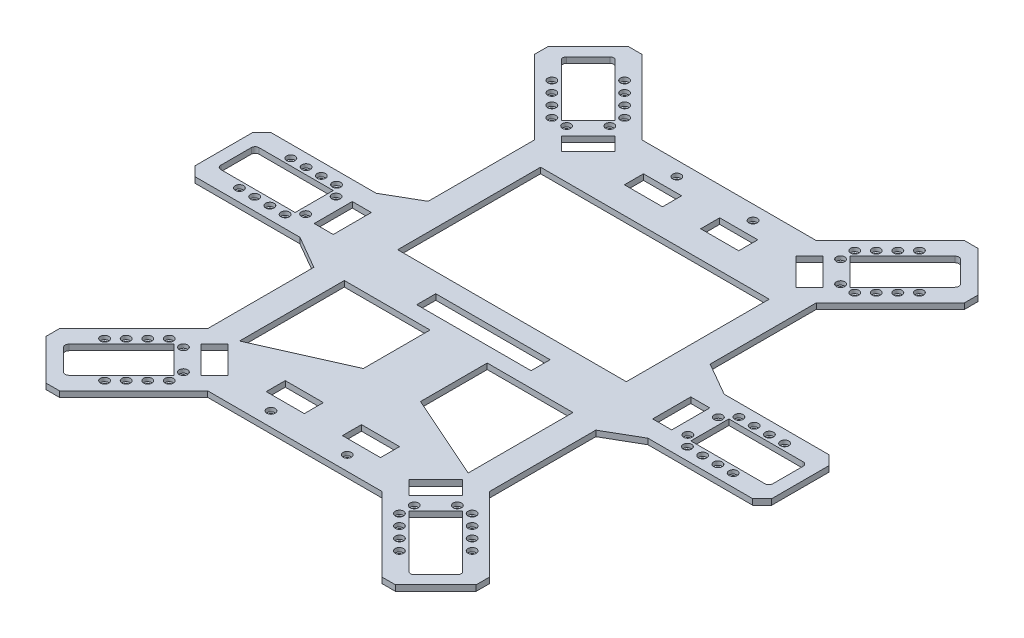
SolidWorks part; units mm, degrees
ref_plane "Front" through (0, 0, 0) normal (0, 0, 1) x (1, 0, 0)
ref_plane "Top" through (0, 0, 0) normal (0, 1, 0) x (1, 0, 0)
ref_plane "Right" through (0, 0, 0) normal (1, 0, 0) x (0, 0, -1)
sketch "草图1" plane through (0, 0, 0) normal (0, 1, 0) x (1, 0, 0)
  line L0 (-45.7157, 114) -> (45.7157, 114)
  line L1 (-74, 0) -> (74, 0) construction
  line L2 (74, -30) -> (91.3205, -20)
  line L3 (91.3205, -20) -> (146.3205, -20)
  line L4 (151.3205, -15) -> (151.3205, 15)
  line L5 (-60, 100) -> (60, -100) construction
  line L6 (-60, -100) -> (60, 100) construction
  line L7 (74, -30) -> (74, -85.7157)
  line L8 (-45.7157, -114) -> (45.7157, -114)
  line L9 (-74, 85.7157) -> (-74, 30)
  line L10 (146.3205, 20) -> (91.3205, 20)
  line L11 (74, 30) -> (91.3205, 20)
  line L12 (0, 100) -> (0, -100) construction
  line L13 (-74, 30) -> (-91.3205, 20)
  line L14 (-146.3205, 20) -> (-91.3205, 20)
  line L15 (-151.3205, -15) -> (-151.3205, 15)
  line L16 (-91.3205, -20) -> (-146.3205, -20)
  line L17 (-74, -30) -> (-91.3205, -20)
  line L18 (-74, -30) -> (-74, -85.7157)
  line L19 (74, 85.7157) -> (74, 30)
  line L20 (91.6777, 152.8909) -> (112.8909, 131.6777)
  line L21 (74, 85.7157) -> (112.8909, 124.6066)
  line L22 (45.7157, 114) -> (84.6066, 152.8909)
  line L23 (-74, 85.7157) -> (-112.8909, 124.6066)
  line L24 (-91.6777, 152.8909) -> (-112.8909, 131.6777)
  line L25 (-45.7157, 114) -> (-84.6066, 152.8909)
  line L26 (74, -85.7157) -> (112.8909, -124.6066)
  line L27 (91.6777, -152.8909) -> (112.8909, -131.6777)
  line L28 (45.7157, -114) -> (84.6066, -152.8909)
  line L29 (-74, -85.7157) -> (-112.8909, -124.6066)
  line L30 (-91.6777, -152.8909) -> (-112.8909, -131.6777)
  line L31 (-45.7157, -114) -> (-84.6066, -152.8909)
  line L32 (-84.6066, 152.8909) -> (-91.6777, 152.8909)
  line L33 (-112.8909, 131.6777) -> (-112.8909, 124.6066)
  line L34 (-151.3205, 15) -> (-146.3205, 20)
  line L35 (-146.3205, -20) -> (-151.3205, -15)
  line L36 (-112.8909, -124.6066) -> (-112.8909, -131.6777)
  line L37 (-84.6066, -152.8909) -> (-91.6777, -152.8909)
  line L38 (84.6066, -152.8909) -> (91.6777, -152.8909)
  line L39 (112.8909, -131.6777) -> (112.8909, -124.6066)
  line L40 (146.3205, -20) -> (151.3205, -15)
  line L41 (151.3205, 15) -> (146.3205, 20)
  line L42 (112.8909, 124.6066) -> (112.8909, 131.6777)
  line L43 (84.6066, 152.8909) -> (91.6777, 152.8909)
  point P0 (0, 0)
  point P12 (74, 30)
  point P16 (74, -30)
extrude "凸台-拉伸1" add sketch "草图1" along normal blind 3
sketch "草图2" plane through (0, 3, 0) normal (0, 1, 0) x (1, 0, 0)
  line L0 (151.3205, 0) -> (87.3942, 0) construction
  line L1 (151.3205, -15) -> (151.3205, 15) construction
  line L2 (103.8205, -10) -> (103.8205, 10)
  line L3 (103.8205, 10) -> (142.8205, 10)
  line L4 (103.8205, -10) -> (142.8205, -10)
  line L5 (144.8205, 8) -> (144.8205, -8)
  arc A0 (144.8205, -8) -> (142.8205, -10) centre (142.8205, -8) cw
  arc A1 (144.8205, 8) -> (142.8205, 10) centre (142.8205, 8) ccw
  point P8 (144.8205, -10)
  point P11 (103.8205, 0)
  dimension "D2" = 2
  dimension "D1" = 41
  dimension "D3" = 20
extrude "切除-拉伸1" cut sketch "草图2" against normal up to next
sketch "草图3" plane through (0, 3, 0) normal (0, 1, 0) x (1, 0, 0)
  line L0 (142.8205, 10) -> (103.8205, 10) construction
  line L1 (103.8205, 10) -> (103.8205, -10) construction
  line L2 (151.3205, 0) -> (86.0016, 0) construction
  line L3 (151.3205, -15) -> (151.3205, 15) construction
  point P0 (105.5705, 13.5)
  point P10 (100.3205, 8)
  point P12 (113.5705, 13.5)
  point P13 (121.5705, 13.5)
  point P14 (129.5705, 13.5)
  point P15 (129.5705, -13.5)
  point P16 (121.5705, -13.5)
  point P17 (113.5705, -13.5)
  point P18 (105.5705, -13.5)
  point P19 (100.3205, -8)
  dimension "D1" = 3.5
  dimension "D2" = 1.75
  dimension "D4" = 3.5
  dimension "D5" = 2
  dimension "D3" = 4
hole_wizard "M2 凹头盖螺钉的柱形沉头孔2" positions "3D草图1" profile "草图9" counterbore size "M2" standard "ANSI Metric" end condition through all
sketch3d "3D草图1"
  point P0 (100.3205, 3, -8)
  point P3 (105.5705, 3, -13.5)
  point P6 (113.5705, 3, -13.5)
  point P9 (121.5705, 3, -13.5)
  point P12 (129.5705, 3, -13.5)
  point P15 (100.3205, 3, 8)
  point P18 (105.5705, 3, 13.5)
  point P21 (113.5705, 3, 13.5)
  point P24 (121.5705, 3, 13.5)
  point P27 (129.5705, 3, 13.5)
sketch "草图9" plane through (100.3205, 3, -8) normal (1, 0, 0) x (0, 0, 1)
  line L0 (0, 0) -> (0, 3)
  line L1 (0, 3) -> (1.2, 3)
  line L3 (1.2, 3) -> (1.2, 2)
  line L4 (1.2, 2) -> (2.2, 2)
  line L5 (2.2, 2) -> (2.2, 0)
  line L7 (2.2, 0) -> (0, 0)
  line L11 (0, -6.35) -> (0, 107.95) construction
  dimension "通孔孔直径" = 2.4
  dimension "通孔孔深度" = 3
  dimension "柱形沉头孔直径" = 4.4
  dimension "柱形沉头孔深度" = 2
sketch "草图10" plane through (0, 3, 0) normal (0, 1, 0) x (1, 0, 0)
  line L0 (102.2843, 142.2843) -> (57.3662, 97.3662) construction
  line L1 (112.8909, 131.6777) -> (91.6777, 152.8909) construction
  line L2 (75.7678, 101.6256) -> (61.6256, 115.7678)
  line L3 (61.6256, 115.7678) -> (89.2028, 143.3449)
  line L4 (75.7678, 101.6256) -> (103.3449, 129.2028)
  line L5 (92.0312, 143.3449) -> (103.3449, 132.0312)
  arc A0 (103.3449, 132.0312) -> (103.3449, 129.2028) centre (101.9307, 130.617) cw
  arc A1 (92.0312, 143.3449) -> (89.2028, 143.3449) centre (90.617, 141.9307) ccw
  point P9 (68.6967, 108.6967)
  dimension "D1" = 2
extrude "切除-拉伸2" cut sketch "草图10" against normal up to next
sketch "草图16" plane through (0, 3, 0) normal (0, 1, 0) x (1, 0, 0)
  line L0 (102.2843, 142.2843) -> (58.019, 98.019) construction
  line L1 (112.8909, 131.6777) -> (91.6777, 152.8909) construction
  line L2 (61.6256, 115.7678) -> (75.7678, 101.6256) construction
  line L3 (89.2028, 143.3449) -> (61.6256, 115.7678) construction
  line L4 (60.3882, 119.4801) -> (80.2149, 139.3067) construction
  point P0 (60.3882, 119.4801)
  point P1 (60.565, 111.8787)
  point P12 (66.045, 125.1369)
  point P13 (71.7019, 130.7938)
  point P14 (77.3588, 136.4506)
  point P15 (96.4506, 117.3588)
  point P16 (90.7938, 111.7019)
  point P17 (85.1369, 106.045)
  point P18 (79.4801, 100.3882)
  point P19 (71.8787, 100.565)
  dimension "D1" = 3.5
  dimension "D2" = 2
  dimension "D3" = 1.75
  dimension "D4" = 3.5
  dimension "D5" = 8
  dimension "D6" = 8
  dimension "D7" = 8
hole_wizard "M2 凹头盖螺钉的柱形沉头孔3" positions "3D草图3" profile "草图17" counterbore size "M2" standard "ANSI Metric" end condition through all
sketch3d "3D草图3"
  point P0 (60.3882, 3, -119.4801)
  point P3 (66.045, 3, -125.1369)
  point P6 (71.7019, 3, -130.7938)
  point P9 (77.3588, 3, -136.4506)
  point P12 (60.565, 3, -111.8787)
  point P15 (71.8787, 3, -100.565)
  point P18 (79.4801, 3, -100.3882)
  point P21 (85.1369, 3, -106.045)
  point P24 (90.7938, 3, -111.7019)
  point P27 (96.4506, 3, -117.3588)
sketch "草图17" plane through (60.3882, 3, -119.4801) normal (1, 0, 0) x (0, 0, 1)
  line L0 (0, 0) -> (0, 3)
  line L1 (0, 3) -> (1.2, 3)
  line L3 (1.2, 3) -> (1.2, 2)
  line L4 (1.2, 2) -> (2.2, 2)
  line L5 (2.2, 2) -> (2.2, 0)
  line L7 (2.2, 0) -> (0, 0)
  line L11 (0, -6.35) -> (0, 107.95) construction
  dimension "通孔孔直径" = 2.4
  dimension "通孔孔深度" = 3
  dimension "柱形沉头孔直径" = 4.4
  dimension "柱形沉头孔深度" = 2
mirror "镜向5" about plane through (0, 0, 0) normal (1, 0, 0) of "切除-拉伸1", "M2 凹头盖螺钉的柱形沉头孔2"
mirror "镜向6" about plane through (0, 0, 0) normal (1, 0, 0) of "切除-拉伸2", "M2 凹头盖螺钉的柱形沉头孔3"
mirror "镜向7" about plane through (0, 0, 0) normal (0, 0, 1) of "切除-拉伸2", "M2 凹头盖螺钉的柱形沉头孔3", "镜向6"
sketch "草图19" plane through (0, 3, 0) normal (0, 1, 0) x (1, 0, 0)
  line L0 (0, 114) -> (0, -114) construction
  line L1 (45.7157, 114) -> (-45.7157, 114) construction
  line L2 (-45.7157, -114) -> (45.7157, -114) construction
  line L3 (-151.3205, 0) -> (151.3205, 0) construction
  line L4 (-30, -89) -> (-10, -89)
  line L5 (-30, -89) -> (-30, -99)
  line L6 (-30, -99) -> (-10, -99)
  line L7 (-10, -89) -> (-10, -99)
  line L8 (-30, 99) -> (-10, 99)
  line L9 (-30, 99) -> (-30, 89)
  line L10 (-30, 89) -> (-10, 89)
  line L11 (-10, 99) -> (-10, 89)
  line L12 (60, 75) -> (-60, 75)
  line L13 (-60, -28) -> (-15, -28)
  line L14 (60, 0) -> (-60, 0)
  line L15 (-60, 75) -> (-60, 0)
  line L16 (30, -10) -> (-30, -10)
  line L17 (-15, -28) -> (-15, -63)
  line L18 (30, -20) -> (-30, -20)
  line L19 (-30, -10) -> (-30, -20)
  line L20 (-151.3205, 15) -> (-151.3205, -15) construction
  line L21 (-60, -83) -> (-15, -63)
  line L22 (60, -83) -> (60, -28)
  line L23 (-60, -83) -> (-60, -28)
  line L24 (60, -83) -> (15, -63)
  line L25 (30, -10) -> (30, -20)
  line L26 (15, -28) -> (15, -63)
  line L27 (60, 75) -> (60, 0)
  line L28 (60, -28) -> (15, -28)
  line L29 (10, 99) -> (10, 89)
  line L30 (30, 89) -> (10, 89)
  line L31 (30, 99) -> (30, 89)
  line L32 (30, 99) -> (10, 99)
  line L33 (10, -89) -> (10, -99)
  line L34 (30, -99) -> (10, -99)
  line L35 (30, -89) -> (30, -99)
  line L36 (30, -89) -> (10, -89)
  point P16 (0, 75)
  point P38 (0, -20)
  point P39 (0, -10)
  point P41 (0, 0)
  dimension "D1" = 60
  dimension "D2" = 8
  dimension "D3" = 10
  dimension "D4" = 0
  dimension "D5" = 55
  dimension "D6" = 35
  dimension "D7" = 45
  dimension "D8" = 10
extrude "切除-拉伸3" cut sketch "草图19" against normal up to next
sketch "草图20" plane through (0, 3, 0) normal (0, 1, 0) x (1, 0, 0)
  line L0 (-68.6967, 108.6967) -> (-55.1555, 95.1555) construction
  line L1 (-61.6256, 115.7678) -> (-75.7678, 101.6256) construction
  line L2 (-103.8205, 0) -> (-73.9191, 0) construction
  line L3 (-103.8205, 10) -> (-103.8205, -10) construction
  line L4 (-47.4835, 101.6256) -> (-54.5546, 108.6967)
  line L5 (-47.4835, 101.6256) -> (-61.6256, 87.4835)
  line L6 (-54.5546, 108.6967) -> (-68.6967, 94.5546)
  line L7 (-61.6256, 87.4835) -> (-68.6967, 94.5546)
  line L8 (-93.8205, -10) -> (-83.8205, -10)
  line L9 (-93.8205, -10) -> (-93.8205, 10)
  line L10 (-83.8205, -10) -> (-83.8205, 10)
  line L11 (-93.8205, 10) -> (-83.8205, 10)
  line L12 (0, 37.6289) -> (0, -38.0523) construction
  line L13 (-21.8368, 0) -> (23.3063, 0) construction
  line L14 (-60, 0) -> (60, 0) construction
  line L15 (47.4835, 101.6256) -> (54.5546, 108.6967)
  line L16 (47.4835, 101.6256) -> (61.6256, 87.4835)
  line L17 (61.6256, 87.4835) -> (68.6967, 94.5546)
  line L18 (54.5546, 108.6967) -> (68.6967, 94.5546)
  line L19 (93.8205, -10) -> (83.8205, -10)
  line L20 (93.8205, -10) -> (93.8205, 10)
  line L21 (83.8205, -10) -> (83.8205, 10)
  line L22 (93.8205, 10) -> (83.8205, 10)
  line L23 (61.6256, -87.4835) -> (68.6967, -94.5546)
  line L24 (54.5546, -108.6967) -> (68.6967, -94.5546)
  line L25 (47.4835, -101.6256) -> (61.6256, -87.4835)
  line L26 (-47.4835, -101.6256) -> (-54.5546, -108.6967)
  line L27 (-47.4835, -101.6256) -> (-61.6256, -87.4835)
  line L28 (-54.5546, -108.6967) -> (-68.6967, -94.5546)
  line L29 (-61.6256, -87.4835) -> (-68.6967, -94.5546)
  line L30 (54.5546, -108.6967) -> (47.4835, -101.6256)
  point P10 (-93.8205, 0)
  point P13 (-54.5546, 94.5546)
  point P16 (-61.6256, 101.6256)
  point P19 (-83.8205, 0)
  point P22 (-93.8205, 0)
  dimension "D1" = 10
  dimension "D2" = 10
  dimension "D3" = 10
  dimension "D4" = 10
  dimension "D5" = 10
  dimension "D6" = 10
extrude "切除-拉伸4" cut sketch "草图20" against normal up to next
sketch "草图21" plane through (0, 3, 0) normal (0, 1, 0) x (1, 0, 0)
  line L2 (45.7157, 114) -> (-45.7157, 114) construction
  line L3 (-30, 99) -> (-30, 89) construction
  line L4 (0, 7.8493) -> (0, -4.9003) construction
  line L5 (-7.8887, 0) -> (8.2893, 0) construction
  line L6 (-60, 0) -> (60, 0) construction
  point P0 (-20, 106.5)
  point P12 (-20, -106.5)
  point P13 (20, 106.5)
  point P14 (20, -106.5)
  dimension "D1" = 7.5
  dimension "D2" = 10
hole_wizard "M2 凹头盖螺钉的柱形沉头孔4" positions "3D草图4" profile "草图22" counterbore size "M2" standard "ANSI Metric" end condition through all
sketch3d "3D草图4"
  point P0 (-20, 3, -106.5)
  point P3 (20, 3, -106.5)
  point P6 (-20, 3, 106.5)
  point P9 (20, 3, 106.5)
sketch "草图22" plane through (-20, 3, -106.5) normal (1, 0, 0) x (0, 0, 1)
  line L0 (0, 0) -> (0, 3)
  line L1 (0, 3) -> (1.2, 3)
  line L3 (1.2, 3) -> (1.2, 2)
  line L4 (1.2, 2) -> (2.2, 2)
  line L5 (2.2, 2) -> (2.2, 0)
  line L7 (2.2, 0) -> (0, 0)
  line L11 (0, -6.35) -> (0, 107.95) construction
  dimension "通孔孔直径" = 2.4
  dimension "通孔孔深度" = 3
  dimension "柱形沉头孔直径" = 4.4
  dimension "柱形沉头孔深度" = 2
